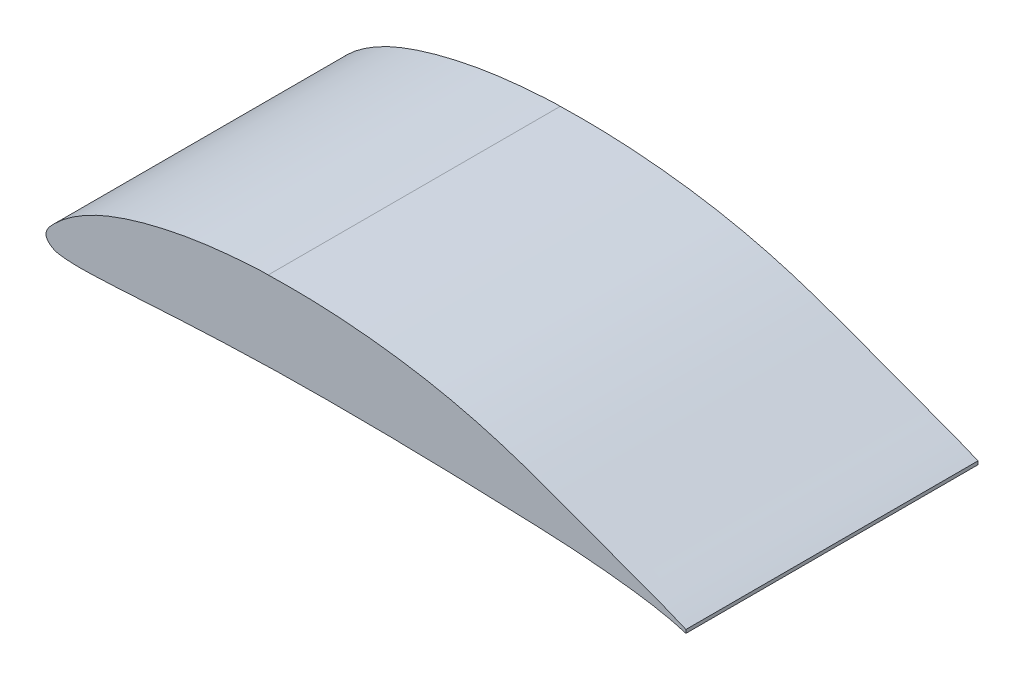
SolidWorks part; units mm, degrees
ref_plane "前视基准面" through (0, 0, 0) normal (0, 0, 1) x (1, 0, 0)
ref_plane "上视基准面" through (0, 0, 0) normal (0, 1, 0) x (1, 0, 0)
ref_plane "右视基准面" through (0, 0, 0) normal (1, 0, 0) x (0, 0, -1)
sketch "草图1" plane through (0, 0, 0) normal (0, 0, 1) x (1, 0, 0)
  line L0 (152.0237, -18.3268) -> (155.1801, -19.2564)
  line L1 (155.1801, -19.2564) -> (114.2823, -19.2564)
  line L2 (114.2823, -19.2564) -> (114.2823, -29.39)
  line L3 (114.2823, -29.39) -> (116.3692, -29.39)
  line L4 (116.3692, -29.39) -> (116.3692, -31.9322)
  line L5 (116.3692, -31.9322) -> (118.3692, -31.9322)
  line L6 (118.3692, -31.9322) -> (118.3692, -37.9517)
  line L7 (118.3692, -37.9517) -> (153.4971, -55.8453)
  line L8 (153.4971, -55.8453) -> (150.2842, -55.7386)
  line L9 (150.2842, -55.7386) -> (143.859, -55.5321)
  line L10 (143.859, -55.5321) -> (137.4346, -55.3337)
  line L11 (137.4346, -55.3337) -> (131.1399, -55.1481)
  line L12 (131.1399, -55.1481) -> (110.0428, -54.6083)
  line L13 (110.0428, -54.6083) -> (105.2941, -54.5059)
  line L14 (105.2941, -54.5059) -> (98.8665, -54.3805)
  line L15 (98.8665, -54.3805) -> (92.4372, -54.2699)
  line L16 (92.4372, -54.2699) -> (86.0082, -54.1744)
  line L17 (86.0082, -54.1744) -> (79.5776, -54.0938)
  line L18 (79.5776, -54.0938) -> (73.1453, -54.0282)
  line L19 (73.1453, -54.0282) -> (66.7084, -53.9784)
  line L20 (66.7084, -53.9784) -> (60.2737, -53.9447)
  line L21 (60.2737, -53.9447) -> (53.8403, -53.929)
  line L22 (53.8403, -53.929) -> (47.4061, -53.9304)
  line L23 (47.4061, -53.9304) -> (40.9731, -53.9508)
  line L24 (40.9731, -53.9508) -> (34.5383, -53.9901)
  line L25 (34.5383, -53.9901) -> (28.1015, -54.0494)
  line L26 (28.1015, -54.0494) -> (21.6579, -54.1294)
  line L27 (21.6579, -54.1294) -> (15.2154, -54.2305)
  line L28 (15.2154, -54.2305) -> (8.7749, -54.3527)
  line L29 (8.7749, -54.3527) -> (3, -54.4812)
  line L30 (3, -54.4812) -> (3, -10.9559)
  line L31 (3, -10.9559) -> (-1, -10.9559)
  line L32 (-1, -10.9559) -> (-1, -54.4059)
  line L33 (-1, -54.4059) -> (-4.1038, -54.4848)
  line L34 (-4.1038, -54.4848) -> (-10.544, -54.67)
  line L35 (-10.544, -54.67) -> (-16.985, -54.8753)
  line L36 (-16.985, -54.8753) -> (-23.4371, -55.103)
  line L37 (-23.4371, -55.103) -> (-29.8851, -55.351)
  line L38 (-29.8851, -55.351) -> (-34.1136, -55.5268)
  line L39 (-34.1136, -55.5268) -> (-55.2107, -56.5131)
  line L40 (-55.2107, -56.5131) -> (-62.1154, -56.8796)
  line L41 (-62.1154, -56.8796) -> (-65.3422, -57.057)
  line L42 (-65.3422, -57.057) -> (-68.5683, -57.2395)
  line L43 (-68.5683, -57.2395) -> (-71.7934, -57.424)
  line L44 (-71.7934, -57.424) -> (-75.0187, -57.6125)
  line L45 (-75.0187, -57.6125) -> (-78.2431, -57.804)
  line L46 (-78.2431, -57.804) -> (-81.4687, -57.9985)
  line L47 (-81.4687, -57.9985) -> (-84.6942, -58.194)
  line L48 (-84.6942, -58.194) -> (-87.9199, -58.3915)
  line L49 (-87.9199, -58.3915) -> (-91.1446, -58.588)
  line L50 (-91.1446, -58.588) -> (-94.3691, -58.7825)
  line L51 (-94.3691, -58.7825) -> (-97.5935, -58.9731)
  line L52 (-97.5935, -58.9731) -> (-100.8186, -59.1566)
  line L53 (-100.8186, -59.1566) -> (-104.0453, -59.331)
  line L54 (-104.0453, -59.331) -> (-107.2725, -59.4944)
  line L55 (-107.2725, -59.4944) -> (-108.8844, -59.5721)
  line L56 (-108.8844, -59.5721) -> (-110.4961, -59.6459)
  line L57 (-110.4961, -59.6459) -> (-112.1078, -59.7177)
  line L58 (-112.1078, -59.7177) -> (-113.7193, -59.7864)
  line L59 (-113.7193, -59.7864) -> (-115.3308, -59.8532)
  line L60 (-115.3308, -59.8532) -> (-116.9421, -59.917)
  line L61 (-116.9421, -59.917) -> (-118.5543, -59.9787)
  line L62 (-118.5543, -59.9787) -> (-120.1635, -60.0386)
  line L63 (-120.1635, -60.0386) -> (-121.7724, -60.0935)
  line L64 (-121.7724, -60.0935) -> (-123.3821, -60.1423)
  line L65 (-123.3821, -60.1423) -> (-124.9913, -60.1811)
  line L66 (-124.9913, -60.1811) -> (-126.601, -60.209)
  line L67 (-126.601, -60.209) -> (-128.2132, -60.2226)
  line L68 (-128.2132, -60.2226) -> (-129.8256, -60.2203)
  line L69 (-129.8256, -60.2203) -> (-131.4362, -60.199)
  line L70 (-131.4362, -60.199) -> (-133.0469, -60.1577)
  line L71 (-133.0469, -60.1577) -> (-134.6557, -60.0945)
  line L72 (-134.6557, -60.0945) -> (-136.2625, -60.0083)
  line L73 (-136.2625, -60.0083) -> (-137.8662, -59.8973)
  line L74 (-137.8662, -59.8973) -> (-139.4657, -59.7594)
  line L75 (-139.4657, -59.7594) -> (-141.059, -59.5937)
  line L76 (-141.059, -59.5937) -> (-141.9501, -59.4867)
  line L77 (-141.9501, -59.4867) -> (-142.8384, -59.3589)
  line L78 (-142.8384, -59.3589) -> (-143.7224, -59.2012)
  line L79 (-143.7224, -59.2012) -> (-144.5995, -59.0017)
  line L80 (-144.5995, -59.0017) -> (-145.4694, -58.7515)
  line L81 (-145.4694, -58.7515) -> (-146.3325, -58.4376)
  line L82 (-146.3325, -58.4376) -> (-147.1845, -58.0511)
  line L83 (-147.1845, -58.0511) -> (-148.1282, -57.5204)
  line L84 (-148.1282, -57.5204) -> (-149.0319, -56.8964)
  line L85 (-149.0319, -56.8964) -> (-149.869, -56.1922)
  line L86 (-149.869, -56.1922) -> (-150.6131, -55.422)
  line L87 (-150.6131, -55.422) -> (-151.2377, -54.597)
  line L88 (-151.2377, -54.597) -> (-151.7174, -53.7322)
  line L89 (-151.7174, -53.7322) -> (-152.0248, -52.84)
  line L90 (-152.0248, -52.84) -> (-152.1253, -51.3832)
  line L91 (-152.1253, -51.3832) -> (-151.7977, -49.9091)
  line L92 (-151.7977, -49.9091) -> (-151.1217, -48.4332)
  line L93 (-151.1217, -48.4332) -> (-150.1773, -46.977)
  line L94 (-150.1773, -46.977) -> (-149.0432, -45.5551)
  line L95 (-149.0432, -45.5551) -> (-147.7983, -44.1871)
  line L96 (-147.7983, -44.1871) -> (-146.5226, -42.8915)
  line L97 (-146.5226, -42.8915) -> (-145.5732, -41.963)
  line L98 (-145.5732, -41.963) -> (-144.6448, -41.0797)
  line L99 (-144.6448, -41.0797) -> (-143.7311, -40.2357)
  line L100 (-143.7311, -40.2357) -> (-142.8238, -39.4235)
  line L101 (-142.8238, -39.4235) -> (-141.9177, -38.6383)
  line L102 (-141.9177, -38.6383) -> (-141.0044, -37.8724)
  line L103 (-141.0044, -37.8724) -> (-140.0777, -37.1201)
  line L104 (-140.0777, -37.1201) -> (-138.5295, -35.9105)
  line L105 (-138.5295, -35.9105) -> (-136.9341, -34.722)
  line L106 (-136.9341, -34.722) -> (-135.2987, -33.5552)
  line L107 (-135.2987, -33.5552) -> (-133.6273, -32.413)
  line L108 (-133.6273, -32.413) -> (-131.928, -31.2971)
  line L109 (-131.928, -31.2971) -> (-130.2069, -30.2101)
  line L110 (-130.2069, -30.2101) -> (-128.4692, -29.1549)
  line L111 (-128.4692, -29.1549) -> (-126.8514, -28.2076)
  line L112 (-126.8514, -28.2076) -> (-125.2257, -27.2876)
  line L113 (-125.2257, -27.2876) -> (-123.5902, -26.3951)
  line L114 (-123.5902, -26.3951) -> (-121.9459, -25.529)
  line L115 (-121.9459, -25.529) -> (-120.2896, -24.6884)
  line L116 (-120.2896, -24.6884) -> (-118.6224, -23.8714)
  line L117 (-118.6224, -23.8714) -> (-116.1374, -22.7102)
  line L118 (-116.1374, -22.7102) -> (-114.5258, -21.9748)
  line L119 (-114.5258, -21.9748) -> (-113.7099, -21.6275)
  line L120 (-113.7099, -21.6275) -> (-112.0779, -20.9311)
  line L121 (-112.0779, -20.9311) -> (-110.4388, -20.2529)
  line L122 (-110.4388, -20.2529) -> (-108.7904, -19.5922)
  line L123 (-108.7904, -19.5922) -> (-107.1357, -18.9477)
  line L124 (-107.1357, -18.9477) -> (-105.4747, -18.3186)
  line L125 (-105.4747, -18.3186) -> (-102.2586, -17.1488)
  line L126 (-102.2586, -17.1488) -> (-99.0258, -16.0327)
  line L127 (-99.0258, -16.0327) -> (-95.7763, -14.9674)
  line L128 (-95.7763, -14.9674) -> (-92.5128, -13.9498)
  line L129 (-92.5128, -13.9498) -> (-89.2343, -12.9779)
  line L130 (-89.2343, -12.9779) -> (-85.9436, -12.0486)
  line L131 (-85.9436, -12.0486) -> (-82.6407, -11.1598)
  line L132 (-82.6407, -11.1598) -> (-79.4154, -10.3297)
  line L133 (-79.4154, -10.3297) -> (-76.1817, -9.536)
  line L134 (-76.1817, -9.536) -> (-72.9396, -8.7777)
  line L135 (-72.9396, -8.7777) -> (-69.6908, -8.0527)
  line L136 (-69.6908, -8.0527) -> (-66.4337, -7.3631)
  line L137 (-66.4337, -7.3631) -> (-63.1689, -6.7059)
  line L138 (-63.1689, -6.7059) -> (-59.8976, -6.082)
  line L139 (-59.8976, -6.082) -> (-53.4763, -4.956)
  line L140 (-53.4763, -4.956) -> (-47.0354, -3.951)
  line L141 (-47.0354, -3.951) -> (-40.5775, -3.0629)
  line L142 (-40.5775, -3.0629) -> (-34.1045, -2.2885)
  line L143 (-34.1045, -2.2885) -> (-27.6182, -1.6208)
  line L144 (-27.6182, -1.6208) -> (-21.1214, -1.0556)
  line L145 (-21.1214, -1.0556) -> (-14.6149, -0.59)
  line L146 (-14.6149, -0.59) -> (-8.1797, -0.2213)
  line L147 (-8.1797, -0.2213) -> (-1, 0.0441)
  line L148 (-1, 0.0441) -> (-1, -3.9559)
  line L149 (-1, -3.9559) -> (3, -3.9559)
  line L150 (3, -3.9559) -> (3, 0.0441)
  line L151 (3, 0.0441) -> (4.6959, 0.069)
  line L152 (4.6959, 0.069) -> (11.1364, 0.1702)
  line L153 (11.1364, 0.1702) -> (17.5773, 0.1873)
  line L154 (17.5773, 0.1873) -> (24.0185, 0.1202)
  line L155 (24.0185, 0.1202) -> (30.4601, -0.0289)
  line L156 (30.4601, -0.0289) -> (36.8903, -0.2576)
  line L157 (36.8903, -0.2576) -> (43.3159, -0.5662)
  line L158 (43.3159, -0.5662) -> (49.7362, -0.9526)
  line L159 (49.7362, -0.9526) -> (56.15, -1.4168)
  line L160 (56.15, -1.4168) -> (62.5595, -1.9579)
  line L161 (62.5595, -1.9579) -> (68.9637, -2.5748)
  line L162 (68.9637, -2.5748) -> (75.3616, -3.2675)
  line L163 (75.3616, -3.2675) -> (81.791, -4.0397)
  line L164 (81.791, -4.0397) -> (88.2081, -4.8894)
  line L165 (88.2081, -4.8894) -> (94.6136, -5.8197)
  line L166 (94.6136, -5.8197) -> (101.0054, -6.8345)
  line L167 (101.0054, -6.8345) -> (107.3835, -7.9338)
  line L168 (107.3835, -7.9338) -> (113.7457, -9.1224)
  line L169 (113.7457, -9.1224) -> (120.0929, -10.4035)
  line L170 (120.0929, -10.4035) -> (126.5261, -11.8004)
  line L171 (126.5261, -11.8004) -> (132.9361, -13.2924)
  line L172 (132.9361, -13.2924) -> (139.323, -14.8785)
  line L173 (139.323, -14.8785) -> (145.6859, -16.5567)
  line L174 (145.6859, -16.5567) -> (152.0237, -18.3268)
  line L175 (118.3692, -37.9517) -> (118.3692, -22.3033)
  line L176 (118.3692, -22.3033) -> (116.3692, -22.3033)
  line L177 (116.3692, -22.3033) -> (116.3692, -29.39)
  line L178 (116.3692, -29.39) -> (114.2823, -29.39)
  line L179 (114.2823, -29.39) -> (114.2823, -19.2564)
  line L180 (114.2823, -19.2564) -> (155.1801, -19.2564)
  line L181 (155.1801, -19.2564) -> (158, -20.0868)
  line L182 (158, -20.0868) -> (158, -25.0868)
  line L183 (158, -25.0868) -> (163, -25.0868)
  line L184 (163, -25.0868) -> (163, -21.6302)
  line L185 (163, -21.6302) -> (164.6237, -22.1331)
  line L186 (164.6237, -22.1331) -> (171.0211, -24.2121)
  line L187 (171.0211, -24.2121) -> (174.8803, -25.5184)
  line L188 (174.8803, -25.5184) -> (174.8803, -32.9368)
  line L189 (174.8803, -32.9368) -> (176.8803, -32.9368)
  line L190 (176.8803, -32.9368) -> (176.8803, -26.1954)
  line L191 (176.8803, -26.1954) -> (178.0562, -26.6012)
  line L192 (178.0562, -26.6012) -> (183.7362, -28.5899)
  line L193 (183.7362, -28.5899) -> (190.063, -30.865)
  line L194 (190.063, -30.865) -> (196.3759, -33.1816)
  line L195 (196.3759, -33.1816) -> (202.6796, -35.5278)
  line L196 (202.6796, -35.5278) -> (208.9785, -37.8918)
  line L197 (208.9785, -37.8918) -> (215.3075, -40.2751)
  line L198 (215.3075, -40.2751) -> (221.6326, -42.6583)
  line L199 (221.6326, -42.6583) -> (227.9578, -45.0395)
  line L200 (227.9578, -45.0395) -> (234.2842, -47.4137)
  line L201 (234.2842, -47.4137) -> (240.6151, -49.7791)
  line L202 (240.6151, -49.7791) -> (246.9514, -52.1327)
  line L203 (246.9514, -52.1327) -> (253.2976, -54.4687)
  line L204 (253.2976, -54.4687) -> (256.4749, -55.6314)
  line L205 (256.4749, -55.6314) -> (259.6502, -56.794)
  line L206 (259.6502, -56.794) -> (262.8233, -57.9606)
  line L207 (262.8233, -57.9606) -> (265.993, -59.1389)
  line L208 (265.993, -59.1389) -> (269.1559, -60.333)
  line L209 (269.1559, -60.333) -> (272.3099, -61.5478)
  line L210 (272.3099, -61.5478) -> (275.4557, -62.7892)
  line L211 (275.4557, -62.7892) -> (278.6394, -64.0813)
  line L212 (278.6394, -64.0813) -> (281.8109, -65.3999)
  line L213 (281.8109, -65.3999) -> (284.9724, -66.742)
  line L214 (284.9724, -66.742) -> (286.0556, -67.2093)
  line L215 (286.0556, -67.2093) -> (286.0556, -69.5328)
  line L216 (286.0556, -69.5328) -> (284.8727, -69.162)
  line L217 (284.8727, -69.162) -> (281.6908, -68.2664)
  line L218 (281.6908, -68.2664) -> (278.4967, -67.4182)
  line L219 (278.4967, -67.4182) -> (275.2881, -66.6285)
  line L220 (275.2881, -66.6285) -> (272.1261, -65.9169)
  line L221 (272.1261, -65.9169) -> (268.9516, -65.2638)
  line L222 (268.9516, -65.2638) -> (265.7658, -64.6633)
  line L223 (265.7658, -64.6633) -> (262.5699, -64.1094)
  line L224 (262.5699, -64.1094) -> (259.3653, -63.5941)
  line L225 (259.3653, -63.5941) -> (256.1553, -63.1116)
  line L226 (256.1553, -63.1116) -> (252.9401, -62.6559)
  line L227 (252.9401, -62.6559) -> (246.5499, -61.8114)
  line L228 (246.5499, -61.8114) -> (240.1543, -61.0427)
  line L229 (240.1543, -61.0427) -> (233.7526, -60.3468)
  line L230 (233.7526, -60.3468) -> (227.3459, -59.7177)
  line L231 (227.3459, -59.7177) -> (220.9334, -59.1545)
  line L232 (220.9334, -59.1545) -> (214.5153, -58.6501)
  line L233 (214.5153, -58.6501) -> (208.0917, -58.2034)
  line L234 (208.0917, -58.2034) -> (201.6737, -57.8101)
  line L235 (201.6737, -57.8101) -> (195.2547, -57.4628)
  line L236 (195.2547, -57.4628) -> (188.835, -57.1555)
  line L237 (188.835, -57.1555) -> (182.414, -56.8791)
  line L238 (182.414, -56.8791) -> (175.9898, -56.6277)
  line L239 (175.9898, -56.6277) -> (169.5649, -56.3942)
  line L240 (169.5649, -56.3942) -> (163.1375, -56.1706)
  line L241 (163.1375, -56.1706) -> (163, -56.1659)
  line L242 (163, -56.1659) -> (163, -50.9959)
  line L243 (163, -50.9959) -> (158, -50.9959)
  line L244 (158, -50.9959) -> (158, -55.9959)
  line L245 (158, -55.9959) -> (156.71, -55.9521)
  line L246 (156.71, -55.9521) -> (153.4971, -55.8453)
  line L247 (153.4971, -55.8453) -> (118.3692, -37.9517)
  line L248 (176.8803, -26.1954) -> (174.8803, -25.5184)
  line L249 (163, -21.6302) -> (158, -20.0868)
  line L250 (163, -56.1659) -> (158, -55.9959)
  line L251 (3, 0.0441) -> (-1, -0.0147)
  line L252 (3, -54.4812) -> (-1, -54.4059)
  line L253 (-1, -3.9559) -> (0, -3.9559)
  line L254 (0, -3.9559) -> (0, 0)
  line L255 (0, 0) -> (2, 0)
  line L256 (2, 0) -> (2, -3.9559)
  line L257 (2, -3.9559) -> (0, -3.9559)
sketch "草图2" plane through (0, 0, 0) normal (0, 0, 1) x (1, 0, 0)
  line L0 (-14.6149, -0.59) -> (-8.1797, -0.2213) construction
  line L1 (286.0556, -67.2093) -> (286.0556, -69.5328)
  spline S0 degree 3 poles (0, 0) (-2.7254, 0.1648) (-6.5293, -0.1383) (-11.397, -0.4053) (-15.7139, -0.6444) (-21.1219, -1.0416) (-27.6196, -1.6029) (-34.106, -2.271) (-40.5798, -3.0436) (-47.0383, -3.9317) (-53.4797, -4.936) (-58.8544, -5.8774) (-63.17, -6.7002) (-66.4344, -7.3579) (-69.692, -8.0463) (-72.9411, -8.7726) (-76.1832, -9.53) (-79.4172, -10.3236) (-82.6712, -11.1618) (-85.9452, -12.0414) (-89.2363, -12.971) (-92.5148, -13.9419) (-95.7791, -14.9599) (-99.0288, -16.0242) (-102.2624, -17.1403) (-104.9625, -18.1217) (-107.1365, -18.9452) (-108.7915, -19.5894) (-110.4392, -20.2501) (-112.0802, -20.926) (-113.4364, -21.5146) (-114.7996, -22.0847) (-116.4298, -22.8496) (-118.3603, -23.7346) (-120.2914, -24.6854) (-121.9485, -25.5247) (-123.5937, -26.392) (-125.2295, -27.284) (-126.8556, -28.2049) (-128.5172, -29.1774) (-130.2108, -30.2054) (-131.9305, -31.2916) (-133.6283, -32.4064) (-135.2985, -33.5465) (-136.9327, -34.7128) (-138.5277, -35.8993) (-139.8798, -36.9561) (-141.0061, -37.8695) (-141.9216, -38.6374) (-142.8307, -39.4252) (-143.7397, -40.2392) (-144.6561, -41.086) (-145.5864, -41.9717) (-146.6414, -43.0038) (-147.814, -44.1864) (-149.0511, -45.5345) (-150.1833, -46.9378) (-151.1378, -48.3803) (-151.8357, -49.854) (-152.198, -51.3579) (-152.1164, -52.6852) (-151.7365, -53.7579) (-151.2487, -54.6228) (-150.6211, -55.445) (-149.8757, -56.2108) (-149.0412, -56.9109) (-148.1414, -57.5317) (-147.2349, -58.0421) (-146.3423, -58.4466) (-145.4769, -58.7603) (-144.6033, -59.0093) (-143.7243, -59.2082) (-142.8393, -59.3636) (-141.9506, -59.4905) (-140.8259, -59.6225) (-139.4649, -59.7643) (-137.8658, -59.9018) (-136.2622, -60.0125) (-134.6556, -60.0983) (-133.0466, -60.1615) (-131.4364, -60.2023) (-129.8251, -60.2236) (-128.2132, -60.2252) (-126.6017, -60.2114) (-124.9913, -60.1828) (-123.3818, -60.1442) (-121.7725, -60.0943) (-120.1633, -60.0396) (-118.5533, -59.9787) (-116.4051, -59.8971) (-114.2563, -59.8096) (-112.1077, -59.7183) (-110.4961, -59.646) (-108.8842, -59.573) (-106.7339, -59.4685) (-104.0451, -59.3331) (-100.8189, -59.158) (-97.5935, -58.9743) (-94.369, -58.7831) (-91.1445, -58.5883) (-87.9195, -58.3917) (-84.6944, -58.1934) (-81.4687, -57.9986) (-78.2436, -57.8034) (-75.0185, -57.6121) (-71.7936, -57.4231) (-68.568, -57.2395) (-65.3421, -57.0559) (-60.8897, -56.812) (-50.4824, -56.2568) (-39.738, -55.7609) (-29.1456, -55.3181) (-23.4361, -55.1001) (-16.9891, -54.8712) (-10.5445, -54.6675) (-5.2161, -54.5116) (24.8162, -53.7512) (54.8641, -53.7858) (86.0077, -54.1717) (92.4374, -54.2674) (98.866, -54.378) (104.7346, -54.4925) (115.4929, -54.7248) (126.2066, -55.0005) (137.478, -55.3335) (143.8594, -55.5311) (149.2135, -55.7021) (153.497, -55.8457) (156.069, -55.93) (159.2825, -56.0398) (163.5676, -56.1844) (169.5643, -56.3927) (175.9899, -56.6246) (182.4135, -56.8749) (188.8353, -57.1505) (195.2555, -57.456) (201.6747, -57.8026) (208.0953, -58.1948) (214.5156, -58.6401) (220.934, -59.1451) (227.3471, -59.7063) (233.7544, -60.3361) (240.1564, -61.0305) (246.5529, -61.799) (251.8849, -62.5035) (256.1556, -63.107) (259.3661, -63.5886) (262.5702, -64.1028) (265.7667, -64.6553) (268.953, -65.255) (272.1283, -65.9071) (275.3111, -66.6228) (278.4998, -67.4069) (282.0905, -68.3717) (284.6152, -69.0618) (286.0556, -69.5328) knots 0 0 0 0 0.013429 0.018717 0.024004 0.034706 0.045405 0.056103 0.066798 0.077493 0.088187 0.098883 0.104347 0.10981 0.115272 0.120733 0.126196 0.131659 0.137123 0.142734 0.148344 0.153954 0.159562 0.165173 0.170784 0.176398 0.179312 0.182225 0.185139 0.188049 0.19096 0.192415 0.195321 0.199821 0.202867 0.205915 0.208964 0.21202 0.215085 0.218161 0.221496 0.224835 0.228171 0.231492 0.234788 0.238052 0.241275 0.243233 0.245189 0.247156 0.249154 0.251194 0.253297 0.255475 0.258458 0.261493 0.264477 0.267324 0.269988 0.272465 0.274861 0.276409 0.278031 0.279729 0.281486 0.283281 0.285082 0.286859 0.288394 0.2899 0.291385 0.292861 0.294334 0.295807 0.297279 0.299907 0.302541 0.305178 0.307818 0.31046 0.313103 0.315746 0.318391 0.321036 0.323677 0.326318 0.32896 0.331601 0.334243 0.33689 0.342182 0.344828 0.347475 0.350122 0.352769 0.358071 0.363372 0.368672 0.373971 0.379271 0.384571 0.389873 0.395175 0.400476 0.405775 0.411076 0.416376 0.421677 0.426979 0.438322 0.472972 0.479916 0.490502 0.501094 0.511666 0.522237 0.52733 0.659527 0.670078 0.680626 0.691176 0.701723 0.709516 0.744139 0.754471 0.765016 0.775562 0.780836 0.78611 0.788228 0.796661 0.807212 0.81776 0.828308 0.838852 0.849396 0.859942 0.870492 0.881056 0.891618 0.902179 0.91274 0.923304 0.933873 0.944448 0.949775 0.955101 0.960426 0.965747 0.971066 0.976383 0.9817 0.987121 0.992543 1 1 1 1
  spline S1 degree 3 poles (0, 0) (3.7124, 0.0371) (9.5705, 0.1861) (17.5776, 0.2001) (24.0193, 0.1343) (30.4575, -0.0157) (36.8905, -0.2441) (43.3162, -0.5533) (49.7366, -0.9395) (56.1516, -1.404) (62.5612, -1.9454) (68.9655, -2.5621) (75.3764, -3.2568) (81.7918, -4.0266) (88.2098, -4.8761) (94.6155, -5.8053) (101.0078, -6.8208) (107.3863, -7.9187) (113.7497, -9.1072) (120.1314, -10.3953) (126.5291, -11.7843) (132.9397, -13.2769) (139.3271, -14.8623) (145.689, -16.5449) (150.9749, -18.0061) (155.0668, -19.2273) (158.7366, -20.2915) (161.874, -21.285) (166.2258, -22.6238) (170.1866, -23.92) (174.2596, -25.3115) (176.6075, -26.0994) (179.5601, -27.1217) (183.9614, -28.6584) (190.0656, -30.8589) (196.3783, -33.1767) (202.6812, -35.5252) (208.9898, -37.8949) (215.3064, -40.2746) (221.6324, -42.6584) (227.9569, -45.0405) (234.284, -47.4153) (240.6147, -49.781) (246.9511, -52.1365) (252.2394, -54.0827) (256.4744, -55.631) (259.6502, -56.7935) (262.8244, -57.9585) (265.9937, -59.1363) (269.1569, -60.3294) (272.3122, -61.5438) (275.4746, -62.7904) (278.6409, -64.0767) (282.1755, -65.5473) (284.6443, -66.5978) (286.0556, -67.2093) knots 0 0 0 0 0.037573 0.059302 0.081033 0.10277 0.124476 0.146178 0.167876 0.18957 0.211269 0.232974 0.254683 0.276529 0.298366 0.320202 0.342035 0.363869 0.385704 0.407548 0.429756 0.451959 0.474159 0.496359 0.518558 0.529658 0.539575 0.557228 0.562962 0.585655 0.5994 0.606523 0.610719 0.631022 0.653703 0.676389 0.69908 0.721776 0.744591 0.767393 0.790194 0.812989 0.835789 0.858592 0.881405 0.892819 0.904226 0.915631 0.927039 0.938445 0.949847 0.961256 0.972847 0.984434 1 1 1 1
extrude "凸台-拉伸1" add sketch "草图2" along normal blind 200
